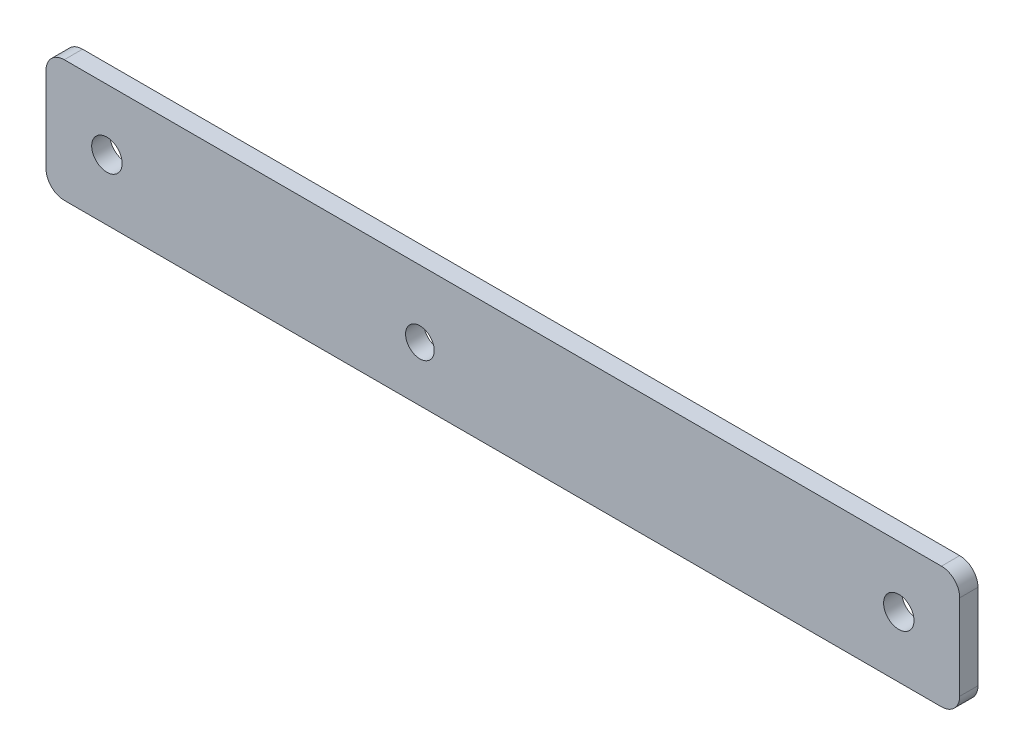
SolidWorks part; units mm, degrees
ref_plane "Top plane" through (0, 0, 0) normal (0, 0, 1) x (1, 0, 0)
ref_plane "Right plane" through (0, 0, 0) normal (0, 1, 0) x (1, 0, 0)
ref_plane "Front plane" through (0, 0, 0) normal (1, 0, 0) x (0, 0, -1)
sketch "Sketch1" plane through (0, 0, 0) normal (0, 0, 1) x (1, 0, 0)
  line L3 (-40, 60) -> (110, 60)
  line L4 (-40, 60) -> (-40, 40)
  line L5 (-40, 40) -> (110, 40)
  line L6 (110, 60) -> (110, 40)
  line L7 (-40, 60) -> (110, 40) construction
  line L8 (-40, 40) -> (110, 60) construction
  circle A0 centre (-30, 50) radius 2.5
  circle A1 centre (100, 50) radius 2.5
  dimension "D3" = 5
  dimension "5" = 5
  dimension "D1" = 20
  dimension "D2" = 150
  dimension "D4" = 10
  dimension "D5" = 10
  dimension "D6" = 10
extrude "Boss-Extrude1" add sketch "Sketch1" along normal blind 3
fillet "Fillet1" radius 3 4 edges at (110, 40, 1.5) (110, 60, 1.5) (-40, 40, 1.5) (-40, 60, 1.5)
sketch "Sketch2" plane through (0, 0, 3) normal (0, 0, 1) x (1, 0, 0)
  circle A0 centre (21.3813, 49.0135) radius 2.3535
  point P2 (0, 0)
  point P3 (18.0397, 46.662)
  point P4 (21.3813, 49.0135)
extrude "Cut-Extrude1" cut sketch "Sketch2" against normal blind 108
